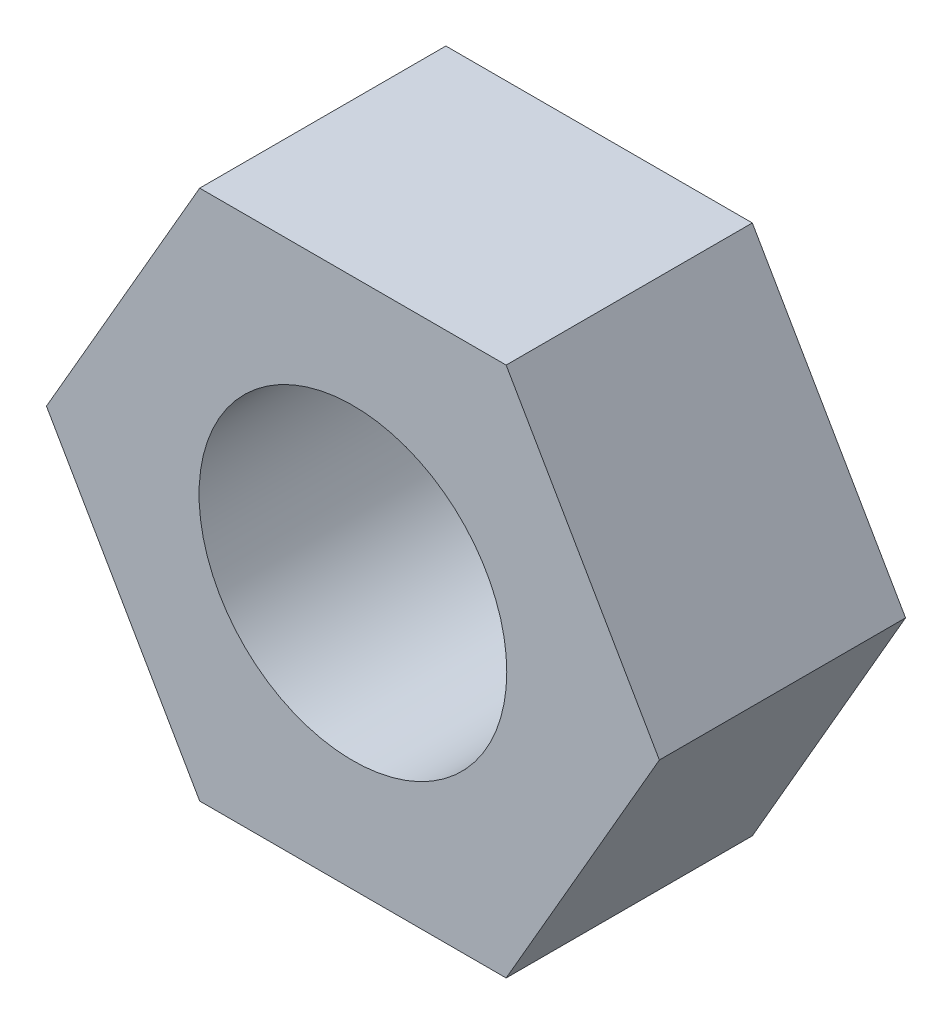
SolidWorks part; units mm, degrees
ref_plane "前视基准面" through (0, 0, 0) normal (0, 0, 1) x (1, 0, 0)
ref_plane "上视基准面" through (0, 0, 0) normal (0, 1, 0) x (1, 0, 0)
ref_plane "右视基准面" through (0, 0, 0) normal (1, 0, 0) x (0, 0, -1)
sketch "草图1" plane through (0, 0, 0) normal (0, 0, 1) x (1, 0, 0)
  line L1 (1.9919, -3.45) -> (3.9837, 0)
  line L2 (3.9837, 0) -> (1.9919, 3.45)
  line L3 (1.9919, 3.45) -> (-1.9919, 3.45)
  line L4 (-1.9919, 3.45) -> (-3.9837, 0)
  line L5 (-3.9837, 0) -> (-1.9919, -3.45)
  line L6 (-1.9919, -3.45) -> (1.9919, -3.45)
  circle A0 centre (0, 0) radius 3.45 construction
  dimension "D1" = 6.9
extrude "凸台-拉伸1" add sketch "草图1" along normal blind 3.2
sketch "草图2" plane through (0, 0, 3.2) normal (0, 0, 1) x (1, 0, 0)
  circle A0 centre (0, 0) radius 2
  dimension "D1" = 4
extrude "切除-拉伸1" cut sketch "草图2" against normal up to next
